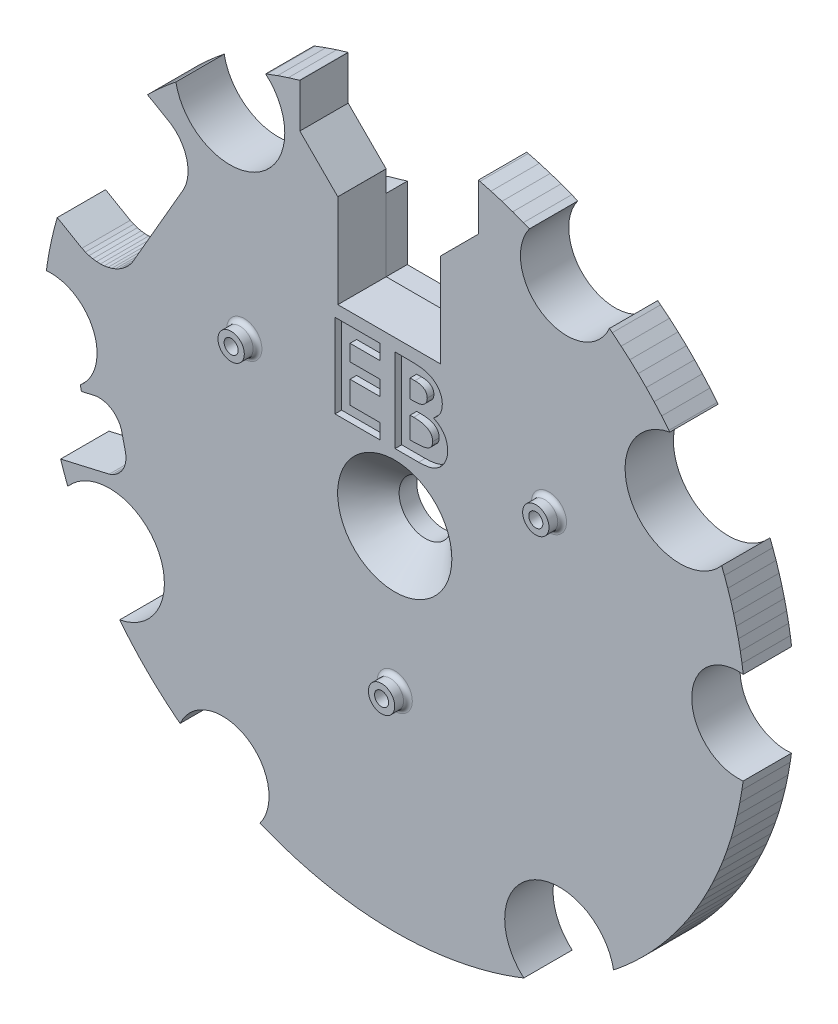
SolidWorks part; units mm, degrees
ref_plane "Płaszczyzna przednia" through (0, 0, 0) normal (0, 0, 1) x (1, 0, 0)
ref_plane "Płaszczyzna górna" through (0, 0, 0) normal (0, 1, 0) x (1, 0, 0)
ref_plane "Płaszczyzna prawa" through (0, 0, 0) normal (1, 0, 0) x (0, 0, -1)
sketch "mandaryna baza " plane through (0, 0, 0) normal (0, 0, 1) x (1, 0, 0)
  line L0 (16.9072, 3.25) -> (54.9039, 3.25)
  line L1 (30.2665, 45.9232) -> (11.2682, 13.017)
  line L2 (5.639, 16.267) -> (24.6374, 49.1732)
  line L3 (-24.6374, 49.1732) -> (-5.639, 16.267)
  line L4 (-11.2682, 13.017) -> (-30.2665, 45.9232)
  line L5 (-54.9039, 3.25) -> (-16.9072, 3.25)
  line L6 (4.5506, 66.6591) -> (4.5491, 66.657) construction
  line L7 (24.4667, 51.9252) -> (4.5506, 66.6591) construction
  line L8 (5.8555, 16.142) -> (24.861, 49.0605) construction
  line L9 (-24.861, 49.0605) -> (-5.8555, 16.142) construction
  line L10 (-4.5491, 66.657) -> (-4.5506, 66.6591) construction
  line L11 (30.0571, 46.0605) -> (11.0517, 13.142) construction
  line L12 (67.2135, 4.9608) -> (71.9198, 8.4424) construction
  line L13 (16.9072, 3) -> (54.9181, 3) construction
  line L14 (-16.9072, -3.25) -> (-54.9039, -3.25)
  line L15 (-30.2665, -45.9232) -> (-11.2682, -13.017)
  line L16 (54.9181, -3) -> (16.9072, -3) construction
  line L17 (71.9198, -8.4424) -> (67.2135, -4.9608) construction
  line L18 (11.0517, -13.142) -> (30.0571, -46.0605) construction
  line L19 (-5.639, -16.267) -> (-24.6374, -49.1732)
  line L20 (24.6374, -49.1732) -> (5.639, -16.267)
  line L21 (11.2682, -13.017) -> (30.2665, -45.9232)
  line L22 (54.9039, -3.25) -> (16.9072, -3.25)
  line L23 (4.5506, -66.6591) -> (24.4667, -51.9252) construction
  line L24 (4.5491, -66.657) -> (4.5506, -66.6591) construction
  line L25 (-4.5506, -66.6591) -> (-4.5491, -66.657) construction
  line L26 (-24.4667, -51.9252) -> (-4.5506, -66.6591) construction
  line L27 (-67.2135, -4.9608) -> (-71.9198, -8.4424) construction
  line L28 (-16.9072, -3) -> (-54.9181, -3) construction
  line L29 (-54.9181, 3) -> (-16.9072, 3) construction
  line L30 (-71.9198, 8.4424) -> (-67.2135, 4.9608) construction
  line L31 (-11.0517, 13.142) -> (-30.0571, 46.0605) construction
  line L37 (-13.1504, 53.4048) -> (-13.1504, 36.9511)
  line L38 (-13.1504, 36.9511) -> (10.6176, 36.9511)
  line L39 (10.6176, 36.9511) -> (10.6176, 53.9654)
  circle A0 centre (0, 0) radius 85 construction
  circle A1 centre (0, 0) radius 6 construction
  arc A2 (11.2682, 13.017) -> (16.9072, 3.25) centre (16.9072, 9.7614) ccw
  arc A3 (-5.639, 16.267) -> (5.639, 16.267) centre (0, 19.5227) ccw
  arc A4 (-16.9072, 3.25) -> (-11.2682, 13.017) centre (-16.9072, 9.7614) ccw
  arc A5 (25.0093, 49.3174) -> (24.4667, 51.9252) centre (23.2772, 50.3174) ccw construction
  arc A6 (-5.8555, 16.142) -> (5.8555, 16.142) centre (0, 19.5227) ccw construction
  arc A7 (-4.5491, 66.657) -> (-0.4915, 64.6309) centre (-0.5295, 69.6307) ccw construction
  arc A8 (0.4915, 64.6309) -> (-0.4915, 64.6309) centre (0, 0) ccw construction
  arc A9 (0.4915, 64.6309) -> (4.5491, 66.657) centre (0.5295, 69.6307) ccw construction
  arc A10 (51.1946, 58.8482) -> (35.971, 56.3035) centre (44.6312, 51.3035) ccw construction
  arc A11 (75.6742, 18.9054) -> (51.1946, 58.8482) centre (0, 0) ccw construction
  arc A12 (71.9198, 8.4424) -> (75.6742, 18.9054) centre (65.9724, 16.4816) ccw construction
  arc A13 (61.2662, 3) -> (67.2135, 4.9608) centre (61.2662, 13) ccw construction
  arc A14 (11.0517, 13.142) -> (16.9072, 3) centre (16.9072, 9.7614) ccw construction
  arc A15 (-11.2682, -13.017) -> (-16.9072, -3.25) centre (-16.9072, -9.7614) ccw
  arc A16 (67.2135, -4.9608) -> (61.2662, -3) centre (61.2662, -13) ccw construction
  arc A17 (75.6742, -18.9054) -> (71.9198, -8.4424) centre (65.9724, -16.4816) ccw construction
  arc A18 (14.9118, -76.5613) -> (56.0831, -54.2097) centre (0, 0) ccw construction
  arc A19 (3, -66.7458) -> (14.9118, -76.5613) centre (13, -66.7458) ccw construction
  arc A20 (16.9072, -3) -> (11.0517, -13.142) centre (16.9072, -9.7614) ccw construction
  arc A21 (5.639, -16.267) -> (-5.639, -16.267) centre (0, -19.5227) ccw
  arc A22 (4.5491, -66.657) -> (0.4915, -64.6309) centre (0.5295, -69.6307) ccw construction
  arc A23 (-0.4915, -64.6309) -> (0.4915, -64.6309) centre (0, 0) ccw construction
  arc A24 (-0.4915, -64.6309) -> (-4.5491, -66.657) centre (-0.5295, -69.6307) ccw construction
  arc A25 (-25.0093, -49.3174) -> (-24.4667, -51.9252) centre (-23.2772, -50.3174) ccw construction
  arc A26 (5.8555, -16.142) -> (-5.8555, -16.142) centre (0, -19.5227) ccw construction
  arc A27 (16.9072, -3.25) -> (11.2682, -13.017) centre (16.9072, -9.7614) ccw
  arc A28 (30.2665, -45.9232) -> (54.9039, -3.25) centre (0, 0) ccw
  arc A29 (24.6374, 49.1732) -> (10.6176, 53.9654) centre (0, 0) ccw
  arc A30 (-51.1946, -58.8482) -> (-35.971, -56.3035) centre (-44.6312, -51.3035) ccw construction
  arc A31 (-75.6742, -18.9054) -> (-51.1946, -58.8482) centre (0, 0) ccw construction
  arc A32 (-71.9198, -8.4424) -> (-75.6742, -18.9054) centre (-65.9724, -16.4816) ccw construction
  arc A33 (-61.2662, -3) -> (-67.2135, -4.9608) centre (-61.2662, -13) ccw construction
  arc A34 (-11.0517, -13.142) -> (-16.9072, -3) centre (-16.9072, -9.7614) ccw construction
  arc A35 (-30.2665, 45.9232) -> (-54.9039, 3.25) centre (0, 0) ccw
  arc A36 (-54.9039, -3.25) -> (-30.2665, -45.9232) centre (0, 0) ccw
  arc A37 (-24.6374, -49.1732) -> (24.6374, -49.1732) centre (0, 0) ccw
  arc A38 (54.9039, 3.25) -> (30.2665, 45.9232) centre (0, 0) ccw
  arc A39 (-67.2135, 4.9608) -> (-61.2662, 3) centre (-61.2662, 13) ccw construction
  arc A40 (-75.6742, 18.9054) -> (-71.9198, 8.4424) centre (-65.9724, 16.4816) ccw construction
  arc A41 (-51.1946, 58.8482) -> (-75.6742, 18.9054) centre (0, 0) ccw construction
  arc A42 (-35.971, 56.3035) -> (-51.1946, 58.8482) centre (-44.6312, 51.3035) ccw construction
  arc A43 (-16.9072, 3) -> (-11.0517, 13.142) centre (-16.9072, 9.7614) ccw construction
  arc A44 (-13.1504, 53.4048) -> (-24.6374, 49.1732) centre (0, 0) ccw
extrude "Dodanie-wyciągnięcie1" add sketch "mandaryna baza " along normal blind 5
sketch "MB_wyciecia" plane through (0, 0, 0) normal (0, 0, 1) x (1, 0, 0)
  line L0 (-0.1242, -22.5327) -> (-0.3125, 0) construction
  line L1 (-34.4185, 20.0049) -> (-0.3125, 0) construction
  line L2 (13.0498, 7.7147) -> (34.7962, 20.27) construction
  line L7 (-35.0924, 72.0577) -> (-32.5738, 67.4522)
  line L8 (-42.3633, 62.4733) -> (-44.721, 66.557)
  line L9 (19.0018, 77.646) -> (19.0018, 67.2099)
  line L10 (19.0018, 67.2099) -> (10.3758, 58.5839)
  line L11 (10.3758, 58.5839) -> (10.3758, 37.3074)
  line L12 (10.3758, 37.3074) -> (-12.9922, 37.3074)
  line L13 (-12.9922, 37.3074) -> (-12.9922, 58.5739)
  line L14 (-12.9922, 58.5739) -> (-21.6382, 67.2099)
  line L15 (-21.6382, 67.2099) -> (-21.7619, 77.0835)
  line L19 (42.2923, -62.1866) -> (44.5033, -66.2834)
  line L20 (-58.3058, 54.9924) -> (-50.9165, 49.4506)
  line L21 (-70.2019, 38.6255) -> (-62.5311, 33.1574)
  line L23 (-74.5615, -9.724) -> (-68.7602, -8.3848)
  line L24 (-76.1011, -24.6775) -> (-65.5639, -22.245)
  line L25 (67.774, 32.961) -> (71.6123, 35.0537)
  line L26 (62.1773, 42.4277) -> (65.9654, 44.8239)
  line L28 (32.3345, -66.7767) -> (34.11, -72.1952)
  line L29 (-62.2802, -42.12) -> (-66.1005, -44.9806)
  line L30 (-67.4562, -32.4335) -> (-72.2043, -34.4007)
  line L31 (-58.3058, 54.9924) -> (-58.3719, 55.055)
  line L32 (-70.2019, 38.6255) -> (-70.3266, 38.7295)
  line L34 (-76.1011, -24.6775) -> (-76.3992, -24.7542)
  line L35 (-72.2043, -34.4007) -> (-72.5196, -34.4687)
  line L36 (-66.1005, -44.9806) -> (-66.3559, -45.1687)
  line L37 (34.11, -72.1952) -> (34.1253, -72.2217)
  arc A1 (-42.3633, 62.4733) -> (-32.5738, 67.4522) centre (-37.5482, 65.1194) ccw
  arc A3 (-62.5311, 33.1574) -> (-50.9165, 49.4506) centre (-56.5654, 41.1911) ccw
  arc A4 (-65.5639, -22.245) -> (-68.7602, -8.3848) centre (-67.0693, -15.2935) ccw
  arc A5 (-62.2802, -42.12) -> (-67.4562, -32.4335) centre (-64.9966, -37.3454) ccw
  arc A7 (62.1773, 42.4277) -> (67.774, 32.961) centre (64.9255, 37.6647) ccw
  arc A8 (42.2923, -62.1866) -> (32.3345, -66.7767) centre (37.4627, -64.8056) ccw
  arc A9 (-21.7619, 77.0835) -> (-35.0924, 72.0577) centre (-0.3125, 0) ccw
  arc A10 (-44.721, 66.557) -> (-58.3719, 55.055) centre (-0.3125, 0) ccw
  arc A11 (-70.3266, 38.7295) -> (-79.6124, 10.6528) centre (-0.3125, 0) ccw
  arc A12 (-76.3992, -24.7542) -> (-72.5196, -34.4687) centre (-0.3125, 0) ccw
  arc A13 (-66.3559, -45.1687) -> (-48.9339, -63.5445) centre (-0.3125, 0) ccw
  arc A14 (44.5033, -66.2834) -> (78.9866, -10.6577) centre (-0.3125, 0) ccw
  arc A15 (65.9654, 44.8239) -> (48.7749, 63.1852) centre (-0.3125, 0) ccw
  arc A16 (79.0174, 10.4265) -> (78.9866, -10.6577) centre (78.1738, -0.1144) ccw
  arc A18 (-30.7368, -74.0021) -> (-48.9339, -63.5445) centre (-39.186, -67.6433) ccw
  arc A21 (30.5908, 73.8033) -> (48.7749, 63.1852) centre (39.186, 67.6433) ccw
  circle A22 centre (38.9878, -67.7577) radius 10.5746
  circle A23 centre (-38.9878, 67.7577) radius 10.5746
  arc A24 (30.5908, 73.8033) -> (19.0018, 77.646) centre (-0.3125, 0) ccw
  arc A25 (79.0174, 10.4265) -> (71.6123, 35.0537) centre (-0.3125, 0) ccw
  arc A26 (-30.7368, -74.0021) -> (34.1253, -72.2217) centre (-0.3125, 0) ccw
  arc A28 (-74.5615, -9.724) -> (-79.6124, 10.6528) centre (-78.3301, 0.1563) ccw
  arc A29 (-84.5664, -8.3092) -> (-82.6226, -9.4789) centre (-78.1738, 0.1144) ccw
  point P46 (0, 0)
  dimension "D6" = 10.9879
  dimension "D7" = 10.9884
  dimension "D8" = 20.013
  dimension "D9" = 14.2253
  dimension "D10" = 10.9979
  dimension "D11" = 160.0243
  dimension "D3" = 80.0122
  dimension "D2" = 39.54
  dimension "D4" = 6
  dimension "D13" = 40.54
  dimension "D15" = 39.54
sketch "EB_" plane through (0, 0, 0) normal (0, 0, 1) x (1, 0, 0)
  line L0 (0, 0) -> (-22.7294, 43.3106) construction
  line L1 (0, 0) -> (25.5306, 43.3106) construction
  line L2 (0, 0) -> (-19.5544, -22.7294)
  line L3 (0, 0) -> (22.3556, -22.7294)
  line L4 (-71.5796, -7.9834) -> (-71.3126, -9.14)
  line L5 (-71.3126, -9.14) -> (-68.5352, -8.4988)
  line L660 (-59.4357, 22.62) -> (-59.654, 22.2418)
  line L661 (-59.654, 22.2418) -> (-60.1628, 21.5318)
  line L662 (-60.1628, 21.5318) -> (-60.7387, 20.8751)
  line L663 (-60.7387, 20.8751) -> (-61.3762, 20.278)
  line L664 (-61.3762, 20.278) -> (-62.0692, 19.7462)
  line L665 (-62.0692, 19.7462) -> (-62.811, 19.285)
  line L666 (-62.811, 19.285) -> (-63.5944, 18.8986)
  line L667 (-63.5944, 18.8986) -> (-64.4119, 18.591)
  line L668 (-64.4119, 18.591) -> (-65.2556, 18.3649)
  line L669 (-65.2556, 18.3649) -> (-66.1174, 18.2226)
  line L670 (-66.1174, 18.2226) -> (-66.989, 18.1655)
  line L671 (-66.989, 18.1655) -> (-67.862, 18.1941)
  line L672 (-67.862, 18.1941) -> (-68.728, 18.3081)
  line L673 (-68.728, 18.3081) -> (-69.5787, 18.5064)
  line L674 (-69.5787, 18.5064) -> (-70.4058, 18.7872)
  line L675 (-70.4058, 18.7872) -> (-71.2014, 19.1477)
  line L676 (-71.2014, 19.1477) -> (-71.5796, 19.366)
  line L677 (-71.5796, 19.366) -> (-76.8174, 22.3901)
  line L678 (-76.8174, 22.3901) -> (-76.8834, 22.1744)
  line L679 (-76.8834, 22.1744) -> (-77.5625, 19.6678)
  line L680 (-77.5625, 19.6678) -> (-78.1599, 17.1405)
  line L681 (-78.1599, 17.1405) -> (-78.6749, 14.5952)
  line L682 (-78.6749, 14.5952) -> (-79.1071, 12.0345)
  line L683 (-79.1071, 12.0345) -> (-79.2897, 10.6872)
  line L693 (-68.5352, -8.4988) -> (-68.1939, -8.42)
  line L694 (-68.1939, -8.42) -> (-67.4966, -8.3528)
  line L695 (-67.4966, -8.3528) -> (-66.7965, -8.3773)
  line L696 (-66.7965, -8.3773) -> (-66.1056, -8.4929)
  line L697 (-66.1056, -8.4929) -> (-65.4357, -8.6977)
  line L698 (-65.4357, -8.6977) -> (-64.7982, -8.9882)
  line L699 (-64.7982, -8.9882) -> (-64.2042, -9.3594)
  line L700 (-64.2042, -9.3594) -> (-63.6636, -9.805)
  line L701 (-63.6636, -9.805) -> (-63.1859, -10.3174)
  line L702 (-63.1859, -10.3174) -> (-62.7791, -10.8877)
  line L703 (-62.7791, -10.8877) -> (-62.4502, -11.5062)
  line L704 (-62.4502, -11.5062) -> (-62.2049, -12.1624)
  line L705 (-62.2049, -12.1624) -> (-62.1261, -12.5037)
  line L706 (-62.1261, -12.5037) -> (-61.3306, -15.949)
  line L707 (-61.3306, -15.949) -> (-61.2518, -16.2903)
  line L708 (-61.2518, -16.2903) -> (-61.1847, -16.9876)
  line L709 (-61.1847, -16.9876) -> (-61.2092, -17.6877)
  line L710 (-61.2092, -17.6877) -> (-61.3248, -18.3787)
  line L711 (-61.3248, -18.3787) -> (-61.5296, -19.0486)
  line L712 (-61.5296, -19.0486) -> (-61.8201, -19.686)
  line L713 (-61.8201, -19.686) -> (-62.1913, -20.2801)
  line L714 (-62.1913, -20.2801) -> (-62.6369, -20.8206)
  line L715 (-62.6369, -20.8206) -> (-63.1492, -21.2984)
  line L716 (-63.1492, -21.2984) -> (-63.7196, -21.7052)
  line L717 (-63.7196, -21.7052) -> (-64.3381, -22.0341)
  line L718 (-64.3381, -22.0341) -> (-64.9942, -22.2794)
  line L719 (-64.9942, -22.2794) -> (-65.3355, -22.3582)
  line L720 (-65.3355, -22.3582) -> (-76.0559, -24.8332)
  line L721 (-76.0559, -24.8332) -> (-75.5463, -26.3728)
  line L722 (-75.5463, -26.3728) -> (-74.6507, -28.8104)
  line L723 (-74.6507, -28.8104) -> (-74.4178, -29.3858)
  line L756 (-62.6093, -49.8114) -> (-61.8317, -50.7929)
  line L757 (-61.8317, -50.7929) -> (-60, -52.944)
  line L758 (-60, -52.944) -> (-58.0936, -55.0292)
  line L759 (-58.0936, -55.0292) -> (-56.1147, -57.0457)
  line L760 (-56.1147, -57.0457) -> (-54.0659, -58.9911)
  line L761 (-54.0659, -58.9911) -> (-51.9496, -60.863)
  line L762 (-51.9496, -60.863) -> (-49.7687, -62.659)
  line L763 (-49.7687, -62.659) -> (-48.854, -63.3595)
  line L770 (-30.6643, -73.9045) -> (-30.3309, -74.048)
  line L771 (-30.3309, -74.048) -> (-27.6979, -75.0726)
  line L772 (-27.6979, -75.0726) -> (-25.0304, -76.0036)
  line L773 (-25.0304, -76.0036) -> (-22.3317, -76.8399)
  line L774 (-22.3317, -76.8399) -> (-19.6051, -77.5804)
  line L775 (-19.6051, -77.5804) -> (-16.8541, -78.2241)
  line L776 (-16.8541, -78.2241) -> (-14.0821, -78.7703)
  line L777 (-14.0821, -78.7703) -> (-11.2926, -79.2184)
  line L778 (-11.2926, -79.2184) -> (-8.4889, -79.5676)
  line L779 (-8.4889, -79.5676) -> (-5.6747, -79.8177)
  line L780 (-5.6747, -79.8177) -> (-2.8534, -79.9683)
  line L781 (-2.8534, -79.9683) -> (-0.0286, -80.0192)
  line L782 (-0.0286, -80.0192) -> (2.7963, -79.9703)
  line L783 (2.7963, -79.9703) -> (5.6177, -79.8218)
  line L784 (5.6177, -79.8218) -> (8.4321, -79.5737)
  line L785 (8.4321, -79.5737) -> (11.236, -79.2264)
  line L786 (11.236, -79.2264) -> (14.0259, -78.7804)
  line L787 (14.0259, -78.7804) -> (16.7983, -78.2361)
  line L788 (16.7983, -78.2361) -> (19.5497, -77.5943)
  line L789 (19.5497, -77.5943) -> (22.2768, -76.8558)
  line L790 (22.2768, -76.8558) -> (24.9761, -76.0215)
  line L791 (24.9761, -76.0215) -> (27.6443, -75.0924)
  line L792 (27.6443, -75.0924) -> (29.3845, -74.4166)
  line L825 (49.8125, -62.6148) -> (50.2037, -62.3107)
  line L826 (50.2037, -62.3107) -> (52.3536, -60.5156)
  line L827 (52.3536, -60.5156) -> (54.4394, -58.6463)
  line L828 (54.4394, -58.6463) -> (56.4584, -56.7052)
  line L829 (56.4584, -56.7052) -> (58.4083, -54.6947)
  line L830 (58.4083, -54.6947) -> (60.2867, -52.6171)
  line L831 (60.2867, -52.6171) -> (62.0911, -50.475)
  line L832 (62.0911, -50.475) -> (63.8195, -48.2711)
  line L833 (63.8195, -48.2711) -> (65.4698, -46.0081)
  line L834 (65.4698, -46.0081) -> (67.0398, -43.6887)
  line L835 (67.0398, -43.6887) -> (68.5277, -41.3158)
  line L836 (68.5277, -41.3158) -> (69.9316, -38.8923)
  line L837 (69.9316, -38.8923) -> (71.2498, -36.4211)
  line L838 (71.2498, -36.4211) -> (72.4808, -33.9053)
  line L839 (72.4808, -33.9053) -> (73.623, -31.348)
  line L840 (73.623, -31.348) -> (74.6749, -28.7523)
  line L841 (74.6749, -28.7523) -> (75.6354, -26.1213)
  line L842 (75.6354, -26.1213) -> (76.5032, -23.4583)
  line L843 (76.5032, -23.4583) -> (77.2773, -20.7666)
  line L844 (77.2773, -20.7666) -> (77.9567, -18.0495)
  line L845 (77.9567, -18.0495) -> (78.5407, -15.3102)
  line L846 (78.5407, -15.3102) -> (79.0284, -12.5522)
  line L847 (79.0284, -12.5522) -> (79.2994, -10.6289)
  line L856 (79.3336, 10.3964) -> (79.0449, 12.4201)
  line L857 (79.0449, 12.4201) -> (78.6613, 14.6547)
  line L858 (78.6613, 14.6547) -> (78.2145, 16.8775)
  line L859 (78.2145, 16.8775) -> (77.7049, 19.0868)
  line L860 (77.7049, 19.0868) -> (77.1329, 21.2808)
  line L861 (77.1329, 21.2808) -> (76.499, 23.4576)
  line L862 (76.499, 23.4576) -> (75.8037, 25.6157)
  line L863 (75.8037, 25.6157) -> (75.0475, 27.7531)
  line L864 (75.0475, 27.7531) -> (74.4174, 29.3854)
  line L897 (62.6156, 49.8127) -> (62.4143, 50.0722)
  line L898 (62.4143, 50.0722) -> (60.7549, 52.0732)
  line L899 (60.7549, 52.0732) -> (59.0313, 54.0192)
  line L900 (59.0313, 54.0192) -> (57.2455, 55.9082)
  line L901 (57.2455, 55.9082) -> (55.3992, 57.7382)
  line L902 (55.3992, 57.7382) -> (53.4945, 59.5072)
  line L903 (53.4945, 59.5072) -> (51.5333, 61.2135)
  line L904 (51.5333, 61.2135) -> (49.5177, 62.8551)
  line L905 (49.5177, 62.8551) -> (48.8544, 63.3604)
  line L913 (30.6602, 73.899) -> (29.2981, 74.4606)
  line L914 (29.2981, 74.4606) -> (26.864, 75.373)
  line L915 (26.864, 75.373) -> (24.4015, 76.2059)
  line L916 (24.4015, 76.2059) -> (21.9132, 76.9583)
  line L917 (21.9132, 76.9583) -> (19.4018, 77.6295)
  line L918 (19.4018, 77.6295) -> (19.0436, 77.7128)
  line L919 (19.0436, 77.7128) -> (19.0437, 67.0537)
  line L920 (19.0437, 67.0537) -> (10.4176, 58.4277)
  line L921 (10.4176, 58.4277) -> (10.4176, 37.1511)
  line L922 (10.4176, 37.1511) -> (-12.9504, 37.1511)
  line L923 (-12.9504, 37.1511) -> (-12.9504, 58.4177)
  line L924 (-12.9504, 58.4177) -> (-12.9604, 58.4177)
  line L925 (-12.9604, 58.4177) -> (-21.5964, 67.0537)
  line L926 (-21.5964, 67.0537) -> (-21.5964, 77.0457)
  line L927 (-21.5964, 77.0457) -> (-21.7211, 77.0127)
  line L928 (-21.7211, 77.0127) -> (-24.2112, 76.2665)
  line L929 (-24.2112, 76.2665) -> (-26.6758, 75.4398)
  line L930 (-26.6758, 75.4398) -> (-29.1122, 74.5335)
  line L931 (-29.1122, 74.5335) -> (-29.3887, 74.4203)
  line L964 (-49.8133, 62.6189) -> (-49.8986, 62.5531)
  line L965 (-49.8986, 62.5531) -> (-51.9022, 60.9009)
  line L966 (-51.9022, 60.9009) -> (-53.8511, 59.1846)
  line L967 (-53.8511, 59.1846) -> (-55.7433, 57.406)
  line L968 (-55.7433, 57.406) -> (-56.2765, 56.8712)
  line L969 (-56.2765, 56.8712) -> (-51.5136, 54.1214)
  line L970 (-51.5136, 54.1214) -> (-51.1354, 53.903)
  line L971 (-51.1354, 53.903) -> (-50.4254, 53.3942)
  line L972 (-50.4254, 53.3942) -> (-49.7687, 52.8183)
  line L973 (-49.7687, 52.8183) -> (-49.1716, 52.1808)
  line L974 (-49.1716, 52.1808) -> (-48.6398, 51.4878)
  line L975 (-48.6398, 51.4878) -> (-48.1786, 50.746)
  line L976 (-48.1786, 50.746) -> (-47.7923, 49.9626)
  line L977 (-47.7923, 49.9626) -> (-47.4846, 49.1452)
  line L978 (-47.4846, 49.1452) -> (-47.2585, 48.3014)
  line L979 (-47.2585, 48.3014) -> (-47.1162, 47.4396)
  line L980 (-47.1162, 47.4396) -> (-47.0591, 46.568)
  line L981 (-47.0591, 46.568) -> (-47.0877, 45.695)
  line L982 (-47.0877, 45.695) -> (-47.2017, 44.829)
  line L983 (-47.2017, 44.829) -> (-47.4, 43.9784)
  line L984 (-47.4, 43.9784) -> (-47.6808, 43.1512)
  line L985 (-47.6808, 43.1512) -> (-48.0413, 42.3556)
  line L986 (-48.0413, 42.3556) -> (-48.2597, 41.9774)
  line L987 (-48.2597, 41.9774) -> (-59.4357, 22.62)
  arc A0 (64.3736, 47.5139) -> (73.3082, 32.0629) centre (64.9348, 37.5297) ccw construction
  circle A3 centre (0, -32.54) radius 1.6
  circle A4 centre (35.1087, 20.27) radius 1.6
  circle A5 centre (-34.2427, 19.77) radius 1.6
  arc A7 (59.3647, 45.8348) -> (-28.5574, 69.3504) centre (0, 0) ccw construction
  arc A9 (-45.8348, 59.3647) -> (-69.3504, -28.5574) centre (0, 0) ccw construction
  arc A10 (-67.5212, -32.6479) -> (69.3504, 28.5574) centre (0, 0) ccw construction
  arc A12 (-30.6643, -73.9045) -> (-48.854, -63.3595) centre (-39.186, -67.6433) ccw
  arc A13 (79.3336, 10.3964) -> (79.2994, -10.6289) centre (78.1738, -0.1144) ccw
  arc A14 (30.6602, 73.899) -> (48.8544, 63.3604) centre (39.186, 67.6433) ccw
  arc A15 (-71.5796, -7.9834) -> (-79.2897, 10.6872) centre (-78.3301, 0.1563) ccw
  arc A16 (62.6156, 49.8127) -> (74.4174, 29.3854) centre (64.9348, 37.5297) ccw
  arc A17 (49.8125, -62.6148) -> (29.3845, -74.4166) centre (37.5297, -64.9348) ccw
  arc A18 (-62.6093, -49.8114) -> (-74.4178, -29.3858) centre (-64.9348, -37.5297) ccw
  arc A19 (-49.8133, 62.6189) -> (-29.3887, 74.4203) centre (-37.5297, 64.9348) ccw
  point P38 (0, 0)
  point P80 (0, 0)
  dimension "D5" = 150
  dimension "D6" = 20
  dimension "D8" = 25
  dimension "D1" = 29.9833
  dimension "D2" = 31.881
  dimension "D3" = 50.2755
  dimension "D4" = 48.9125
  dimension "D9" = 4
extrude "Dodanie-wyciągnięcie2" add sketch "EB_" along direction (0, 0, 1) on the side of the normal blind 11 from offset 5
sketch "Szkic5" plane through (0, 0, 16) normal (0, 0, 1) x (1, 0, 0)
  circle A0 centre (-34.2427, 19.77) radius 1.6
  circle A1 centre (-34.2427, 19.77) radius 3
  circle A2 centre (35.1087, 20.27) radius 1.6
  circle A3 centre (35.1087, 20.27) radius 3
  circle A4 centre (0, -32.54) radius 1.6
  circle A5 centre (0, -32.54) radius 3
  dimension "D1" = 6
  dimension "D2" = 3.2
  dimension "D3" = 6
  dimension "D4" = 3.2
  dimension "D5" = 6
  dimension "D6" = 3.2
extrude "Dodanie-wyciągnięcie3" add sketch "Szkic5" along normal blind 3
sketch "Szkic6" plane through (0, 0, 16) normal (0, 0, 1) x (1, 0, 0)
  circle A0 centre (0, -32.54) radius 1.6 construction
  circle A1 centre (35.1087, 20.27) radius 1.6 construction
  circle A2 centre (-34.2427, 19.77) radius 1.6 construction
  circle A3 centre (0, -32.54) radius 1.6
  circle A4 centre (35.1087, 20.27) radius 1.6
  circle A5 centre (-34.2427, 19.77) radius 1.6
extrude "Wytnij-wyciągnięcie1" cut sketch "Szkic6" against normal through all
sketch "Szkic7" plane through (0, 0, 16) normal (0, 0, 1) x (1, 0, 0)
  circle A0 centre (0, 0) radius 6
  dimension "D1" = 12
extrude "Wytnij-wyciągnięcie2" cut sketch "Szkic7" against normal through all
chamfer "Sfazowanie1" distance 7 angle 45 1 edges at (6, 0, 16)
sketch "Szkic8" plane through (0, 0, 16) normal (0, 0, 1) x (1, 0, 0)
  line L181 (-71.5796, -7.9834) -> (-71.3126, -9.14)
  line L182 (-71.3126, -9.14) -> (-68.5352, -8.4988)
  line L183 (-68.5352, -8.4988) -> (-68.1939, -8.42)
  line L184 (-68.1939, -8.42) -> (-67.4966, -8.3528)
  line L185 (-67.4966, -8.3528) -> (-66.7965, -8.3773)
  line L186 (-66.7965, -8.3773) -> (-66.1056, -8.4929)
  line L187 (-66.1056, -8.4929) -> (-65.4357, -8.6977)
  line L188 (-65.4357, -8.6977) -> (-64.7982, -8.9882)
  line L189 (-64.7982, -8.9882) -> (-64.2042, -9.3594)
  line L190 (-64.2042, -9.3594) -> (-63.6636, -9.805)
  line L191 (-63.6636, -9.805) -> (-63.1859, -10.3174)
  line L192 (-63.1859, -10.3174) -> (-62.7791, -10.8877)
  line L193 (-62.7791, -10.8877) -> (-62.4502, -11.5062)
  line L194 (-62.4502, -11.5062) -> (-62.2049, -12.1624)
  line L195 (-62.2049, -12.1624) -> (-62.1261, -12.5037)
  line L196 (-62.1261, -12.5037) -> (-61.3306, -15.949)
  line L197 (-61.3306, -15.949) -> (-61.2518, -16.2903)
  line L198 (-61.2518, -16.2903) -> (-61.1847, -16.9876)
  line L199 (-61.1847, -16.9876) -> (-61.2092, -17.6877)
  line L200 (-61.2092, -17.6877) -> (-61.3248, -18.3787)
  line L201 (-61.3248, -18.3787) -> (-61.5296, -19.0486)
  line L202 (-61.5296, -19.0486) -> (-61.8201, -19.686)
  line L203 (-61.8201, -19.686) -> (-62.1913, -20.2801)
  line L204 (-62.1913, -20.2801) -> (-62.6369, -20.8206)
  line L205 (-62.6369, -20.8206) -> (-63.1492, -21.2984)
  line L206 (-63.1492, -21.2984) -> (-63.7196, -21.7052)
  line L207 (-63.7196, -21.7052) -> (-64.3381, -22.0341)
  line L208 (-64.3381, -22.0341) -> (-64.9942, -22.2794)
  line L209 (-64.9942, -22.2794) -> (-65.3355, -22.3582)
  line L210 (-65.3355, -22.3582) -> (-76.0559, -24.8332)
  line L211 (-76.0559, -24.8332) -> (-75.5463, -26.3728)
  line L212 (-75.5463, -26.3728) -> (-74.6507, -28.8104)
  line L213 (-74.6507, -28.8104) -> (-74.4178, -29.3858)
  line L216 (-62.6093, -49.8114) -> (-61.8317, -50.7929)
  line L217 (-61.8317, -50.7929) -> (-60, -52.944)
  line L218 (-60, -52.944) -> (-58.0936, -55.0292)
  line L219 (-58.0936, -55.0292) -> (-56.1147, -57.0457)
  line L220 (-56.1147, -57.0457) -> (-54.0659, -58.9911)
  line L221 (-54.0659, -58.9911) -> (-51.9496, -60.863)
  line L222 (-51.9496, -60.863) -> (-49.7687, -62.659)
  line L223 (-49.7687, -62.659) -> (-48.854, -63.3595)
  line L224 (-30.6643, -73.9045) -> (-30.3309, -74.048)
  line L225 (-30.3309, -74.048) -> (-27.6979, -75.0726)
  line L226 (-27.6979, -75.0726) -> (-25.0304, -76.0036)
  line L227 (-25.0304, -76.0036) -> (-22.3317, -76.8399)
  line L228 (-22.3317, -76.8399) -> (-19.6051, -77.5804)
  line L229 (-19.6051, -77.5804) -> (-16.8541, -78.2241)
  line L230 (-16.8541, -78.2241) -> (-14.0821, -78.7703)
  line L231 (-14.0821, -78.7703) -> (-11.2926, -79.2184)
  line L232 (-11.2926, -79.2184) -> (-8.4889, -79.5676)
  line L233 (-8.4889, -79.5676) -> (-5.6747, -79.8177)
  line L234 (-5.6747, -79.8177) -> (-2.8534, -79.9683)
  line L235 (-2.8534, -79.9683) -> (-0.0286, -80.0192)
  line L236 (-0.0286, -80.0192) -> (2.7963, -79.9703)
  line L237 (2.7963, -79.9703) -> (5.6177, -79.8218)
  line L238 (5.6177, -79.8218) -> (8.4321, -79.5737)
  line L239 (8.4321, -79.5737) -> (11.236, -79.2264)
  line L240 (11.236, -79.2264) -> (14.0259, -78.7804)
  line L241 (14.0259, -78.7804) -> (16.7983, -78.2361)
  line L242 (16.7983, -78.2361) -> (19.5497, -77.5943)
  line L243 (19.5497, -77.5943) -> (22.2768, -76.8558)
  line L244 (22.2768, -76.8558) -> (24.9761, -76.0215)
  line L245 (24.9761, -76.0215) -> (27.6443, -75.0924)
  line L246 (27.6443, -75.0924) -> (29.3845, -74.4166)
  line L249 (49.8125, -62.6148) -> (50.2037, -62.3107)
  line L250 (50.2037, -62.3107) -> (52.3536, -60.5156)
  line L251 (52.3536, -60.5156) -> (54.4394, -58.6463)
  line L252 (54.4394, -58.6463) -> (56.4584, -56.7052)
  line L253 (56.4584, -56.7052) -> (58.4083, -54.6947)
  line L254 (58.4083, -54.6947) -> (60.2867, -52.6171)
  line L255 (60.2867, -52.6171) -> (62.0911, -50.475)
  line L256 (62.0911, -50.475) -> (63.8195, -48.2711)
  line L257 (63.8195, -48.2711) -> (65.4698, -46.0081)
  line L258 (65.4698, -46.0081) -> (67.0398, -43.6887)
  line L259 (67.0398, -43.6887) -> (68.5277, -41.3158)
  line L260 (68.5277, -41.3158) -> (69.9316, -38.8923)
  line L261 (69.9316, -38.8923) -> (71.2498, -36.4211)
  line L262 (71.2498, -36.4211) -> (72.4808, -33.9053)
  line L263 (72.4808, -33.9053) -> (73.623, -31.348)
  line L264 (73.623, -31.348) -> (74.6749, -28.7523)
  line L265 (74.6749, -28.7523) -> (75.6354, -26.1213)
  line L266 (75.6354, -26.1213) -> (76.5032, -23.4583)
  line L267 (76.5032, -23.4583) -> (77.2773, -20.7666)
  line L268 (77.2773, -20.7666) -> (77.9567, -18.0495)
  line L269 (77.9567, -18.0495) -> (78.5407, -15.3102)
  line L270 (78.5407, -15.3102) -> (79.0284, -12.5522)
  line L271 (79.0284, -12.5522) -> (79.2994, -10.6289)
  line L272 (79.3336, 10.3964) -> (79.0449, 12.4201)
  line L273 (79.0449, 12.4201) -> (78.6613, 14.6547)
  line L274 (78.6613, 14.6547) -> (78.2145, 16.8775)
  line L275 (78.2145, 16.8775) -> (77.7049, 19.0868)
  line L276 (77.7049, 19.0868) -> (77.1329, 21.2808)
  line L277 (77.1329, 21.2808) -> (76.499, 23.4576)
  line L278 (76.499, 23.4576) -> (75.8037, 25.6157)
  line L279 (75.8037, 25.6157) -> (75.0475, 27.7531)
  line L280 (75.0475, 27.7531) -> (74.4174, 29.3854)
  line L284 (62.6156, 49.8127) -> (62.4143, 50.0722)
  line L285 (62.4143, 50.0722) -> (60.7549, 52.0732)
  line L286 (60.7549, 52.0732) -> (59.0313, 54.0192)
  line L287 (59.0313, 54.0192) -> (57.2455, 55.9082)
  line L288 (57.2455, 55.9082) -> (55.3992, 57.7382)
  line L289 (55.3992, 57.7382) -> (53.4945, 59.5072)
  line L290 (53.4945, 59.5072) -> (51.5333, 61.2135)
  line L291 (51.5333, 61.2135) -> (49.5177, 62.8551)
  line L292 (49.5177, 62.8551) -> (48.8544, 63.3604)
  line L293 (30.6602, 73.899) -> (29.2981, 74.4606)
  line L294 (29.2981, 74.4606) -> (26.864, 75.373)
  line L295 (26.864, 75.373) -> (24.4015, 76.2059)
  line L296 (24.4015, 76.2059) -> (21.9132, 76.9583)
  line L297 (21.9132, 76.9583) -> (19.4018, 77.6295)
  line L298 (19.4018, 77.6295) -> (19.0436, 77.7128)
  line L299 (19.0436, 77.7128) -> (19.0437, 67.0537)
  line L300 (19.0437, 67.0537) -> (10.4176, 58.4277)
  line L301 (10.4176, 58.4277) -> (10.4176, 37.1511)
  line L302 (10.4176, 37.1511) -> (-12.9504, 37.1511)
  line L303 (-12.9504, 37.1511) -> (-12.9504, 58.4177)
  line L304 (-12.9504, 58.4177) -> (-12.9604, 58.4177)
  line L305 (-12.9604, 58.4177) -> (-21.5964, 67.0537)
  line L306 (-21.5964, 67.0537) -> (-21.5964, 77.0457)
  line L307 (-21.5964, 77.0457) -> (-21.7211, 77.0127)
  line L308 (-21.7211, 77.0127) -> (-24.2112, 76.2665)
  line L309 (-24.2112, 76.2665) -> (-26.6758, 75.4398)
  line L310 (-26.6758, 75.4398) -> (-29.1122, 74.5335)
  line L311 (-29.1122, 74.5335) -> (-29.3887, 74.4203)
  line L314 (-49.8133, 62.6189) -> (-49.8986, 62.5531)
  line L315 (-49.8986, 62.5531) -> (-51.9022, 60.9009)
  line L316 (-51.9022, 60.9009) -> (-53.8511, 59.1846)
  line L317 (-53.8511, 59.1846) -> (-55.7433, 57.406)
  line L318 (-55.7433, 57.406) -> (-56.2765, 56.8712)
  line L319 (-56.2765, 56.8712) -> (-51.5136, 54.1214)
  line L320 (-51.5136, 54.1214) -> (-51.1354, 53.903)
  line L321 (-51.1354, 53.903) -> (-50.4254, 53.3942)
  line L322 (-50.4254, 53.3942) -> (-49.7687, 52.8183)
  line L323 (-49.7687, 52.8183) -> (-49.1716, 52.1808)
  line L324 (-49.1716, 52.1808) -> (-48.6398, 51.4878)
  line L325 (-48.6398, 51.4878) -> (-48.1786, 50.746)
  line L326 (-48.1786, 50.746) -> (-47.7923, 49.9626)
  line L327 (-47.7923, 49.9626) -> (-47.4846, 49.1452)
  line L328 (-47.4846, 49.1452) -> (-47.2585, 48.3014)
  line L329 (-47.2585, 48.3014) -> (-47.1162, 47.4396)
  line L330 (-47.1162, 47.4396) -> (-47.0591, 46.568)
  line L331 (-47.0591, 46.568) -> (-47.0877, 45.695)
  line L332 (-47.0877, 45.695) -> (-47.2017, 44.829)
  line L333 (-47.2017, 44.829) -> (-47.4, 43.9784)
  line L334 (-47.4, 43.9784) -> (-47.6808, 43.1512)
  line L335 (-47.6808, 43.1512) -> (-48.0413, 42.3556)
  line L336 (-48.0413, 42.3556) -> (-48.2597, 41.9774)
  line L337 (-48.2597, 41.9774) -> (-59.4357, 22.62)
  line L338 (-59.4357, 22.62) -> (-59.654, 22.2418)
  line L339 (-59.654, 22.2418) -> (-60.1628, 21.5318)
  line L340 (-60.1628, 21.5318) -> (-60.7387, 20.8751)
  line L341 (-60.7387, 20.8751) -> (-61.3762, 20.278)
  line L342 (-61.3762, 20.278) -> (-62.0692, 19.7462)
  line L343 (-62.0692, 19.7462) -> (-62.811, 19.285)
  line L344 (-62.811, 19.285) -> (-63.5944, 18.8986)
  line L345 (-63.5944, 18.8986) -> (-64.4119, 18.591)
  line L346 (-64.4119, 18.591) -> (-65.2556, 18.3649)
  line L347 (-65.2556, 18.3649) -> (-66.1174, 18.2226)
  line L348 (-66.1174, 18.2226) -> (-66.989, 18.1655)
  line L349 (-66.989, 18.1655) -> (-67.862, 18.1941)
  line L350 (-67.862, 18.1941) -> (-68.728, 18.3081)
  line L351 (-68.728, 18.3081) -> (-69.5787, 18.5064)
  line L352 (-69.5787, 18.5064) -> (-70.4058, 18.7872)
  line L353 (-70.4058, 18.7872) -> (-71.2014, 19.1477)
  line L354 (-71.2014, 19.1477) -> (-71.5796, 19.366)
  line L355 (-71.5796, 19.366) -> (-76.8174, 22.3901)
  line L356 (-76.8174, 22.3901) -> (-76.8834, 22.1744)
  line L357 (-76.8834, 22.1744) -> (-77.5625, 19.6678)
  line L358 (-77.5625, 19.6678) -> (-78.1599, 17.1405)
  line L359 (-78.1599, 17.1405) -> (-78.6749, 14.5952)
  line L360 (-78.6749, 14.5952) -> (-79.1071, 12.0345)
  line L361 (-79.1071, 12.0345) -> (-79.2897, 10.6872)
  line L362 (-71.5796, -7.9834) -> (-71.3126, -9.14)
  line L363 (-71.3126, -9.14) -> (-68.5352, -8.4988)
  line L364 (-68.5352, -8.4988) -> (-68.1939, -8.42)
  line L365 (-68.1939, -8.42) -> (-67.4966, -8.3528)
  line L366 (-67.4966, -8.3528) -> (-66.7965, -8.3773)
  line L367 (-66.7965, -8.3773) -> (-66.1056, -8.4929)
  line L368 (-66.1056, -8.4929) -> (-65.4357, -8.6977)
  line L369 (-65.4357, -8.6977) -> (-64.7982, -8.9882)
  line L370 (-64.7982, -8.9882) -> (-64.2042, -9.3594)
  line L371 (-64.2042, -9.3594) -> (-63.6636, -9.805)
  line L372 (-63.6636, -9.805) -> (-63.1859, -10.3174)
  line L373 (-63.1859, -10.3174) -> (-62.7791, -10.8877)
  line L374 (-62.7791, -10.8877) -> (-62.4502, -11.5062)
  line L375 (-62.4502, -11.5062) -> (-62.2049, -12.1624)
  line L376 (-62.2049, -12.1624) -> (-62.1261, -12.5037)
  line L377 (-62.1261, -12.5037) -> (-61.3306, -15.949)
  line L378 (-61.3306, -15.949) -> (-61.2518, -16.2903)
  line L379 (-61.2518, -16.2903) -> (-61.1847, -16.9876)
  line L380 (-61.1847, -16.9876) -> (-61.2092, -17.6877)
  line L381 (-61.2092, -17.6877) -> (-61.3248, -18.3787)
  line L382 (-61.3248, -18.3787) -> (-61.5296, -19.0486)
  line L383 (-61.5296, -19.0486) -> (-61.8201, -19.686)
  line L384 (-61.8201, -19.686) -> (-62.1913, -20.2801)
  line L385 (-62.1913, -20.2801) -> (-62.6369, -20.8206)
  line L386 (-62.6369, -20.8206) -> (-63.1492, -21.2984)
  line L387 (-63.1492, -21.2984) -> (-63.7196, -21.7052)
  line L388 (-63.7196, -21.7052) -> (-64.3381, -22.0341)
  line L389 (-64.3381, -22.0341) -> (-64.9942, -22.2794)
  line L390 (-64.9942, -22.2794) -> (-65.3355, -22.3582)
  line L391 (-65.3355, -22.3582) -> (-76.0559, -24.8332)
  line L392 (-76.0559, -24.8332) -> (-75.5463, -26.3728)
  line L393 (-75.5463, -26.3728) -> (-74.6507, -28.8104)
  line L394 (-74.6507, -28.8104) -> (-74.4178, -29.3858)
  line L397 (-62.6093, -49.8114) -> (-61.8317, -50.7929)
  line L398 (-61.8317, -50.7929) -> (-60, -52.944)
  line L399 (-60, -52.944) -> (-58.0936, -55.0292)
  line L400 (-58.0936, -55.0292) -> (-56.1147, -57.0457)
  line L401 (-56.1147, -57.0457) -> (-54.0659, -58.9911)
  line L402 (-54.0659, -58.9911) -> (-51.9496, -60.863)
  line L403 (-51.9496, -60.863) -> (-49.7687, -62.659)
  line L404 (-49.7687, -62.659) -> (-48.854, -63.3595)
  line L405 (-30.6643, -73.9045) -> (-30.3309, -74.048)
  line L406 (-30.3309, -74.048) -> (-27.6979, -75.0726)
  line L407 (-27.6979, -75.0726) -> (-25.0304, -76.0036)
  line L408 (-25.0304, -76.0036) -> (-22.3317, -76.8399)
  line L409 (-22.3317, -76.8399) -> (-19.6051, -77.5804)
  line L410 (-19.6051, -77.5804) -> (-16.8541, -78.2241)
  line L411 (-16.8541, -78.2241) -> (-14.0821, -78.7703)
  line L412 (-14.0821, -78.7703) -> (-11.2926, -79.2184)
  line L413 (-11.2926, -79.2184) -> (-8.4889, -79.5676)
  line L414 (-8.4889, -79.5676) -> (-5.6747, -79.8177)
  line L415 (-5.6747, -79.8177) -> (-2.8534, -79.9683)
  line L416 (-2.8534, -79.9683) -> (-0.0286, -80.0192)
  line L417 (-0.0286, -80.0192) -> (2.7963, -79.9703)
  line L418 (2.7963, -79.9703) -> (5.6177, -79.8218)
  line L419 (5.6177, -79.8218) -> (8.4321, -79.5737)
  line L420 (8.4321, -79.5737) -> (11.236, -79.2264)
  line L421 (11.236, -79.2264) -> (14.0259, -78.7804)
  line L422 (14.0259, -78.7804) -> (16.7983, -78.2361)
  line L423 (16.7983, -78.2361) -> (19.5497, -77.5943)
  line L424 (19.5497, -77.5943) -> (22.2768, -76.8558)
  line L425 (22.2768, -76.8558) -> (24.9761, -76.0215)
  line L426 (24.9761, -76.0215) -> (27.6443, -75.0924)
  line L427 (27.6443, -75.0924) -> (29.3845, -74.4166)
  line L430 (49.8125, -62.6148) -> (50.2037, -62.3107)
  line L431 (50.2037, -62.3107) -> (52.3536, -60.5156)
  line L432 (52.3536, -60.5156) -> (54.4394, -58.6463)
  line L433 (54.4394, -58.6463) -> (56.4584, -56.7052)
  line L434 (56.4584, -56.7052) -> (58.4083, -54.6947)
  line L435 (58.4083, -54.6947) -> (60.2867, -52.6171)
  line L436 (60.2867, -52.6171) -> (62.0911, -50.475)
  line L437 (62.0911, -50.475) -> (63.8195, -48.2711)
  line L438 (63.8195, -48.2711) -> (65.4698, -46.0081)
  line L439 (65.4698, -46.0081) -> (67.0398, -43.6887)
  line L440 (67.0398, -43.6887) -> (68.5277, -41.3158)
  line L441 (68.5277, -41.3158) -> (69.9316, -38.8923)
  line L442 (69.9316, -38.8923) -> (71.2498, -36.4211)
  line L443 (71.2498, -36.4211) -> (72.4808, -33.9053)
  line L444 (72.4808, -33.9053) -> (73.623, -31.348)
  line L445 (73.623, -31.348) -> (74.6749, -28.7523)
  line L446 (74.6749, -28.7523) -> (75.6354, -26.1213)
  line L447 (75.6354, -26.1213) -> (76.5032, -23.4583)
  line L448 (76.5032, -23.4583) -> (77.2773, -20.7666)
  line L449 (77.2773, -20.7666) -> (77.9567, -18.0495)
  line L450 (77.9567, -18.0495) -> (78.5407, -15.3102)
  line L451 (78.5407, -15.3102) -> (79.0284, -12.5522)
  line L452 (79.0284, -12.5522) -> (79.2994, -10.6289)
  line L453 (79.3336, 10.3964) -> (79.0449, 12.4201)
  line L454 (79.0449, 12.4201) -> (78.6613, 14.6547)
  line L455 (78.6613, 14.6547) -> (78.2145, 16.8775)
  line L456 (78.2145, 16.8775) -> (77.7049, 19.0868)
  line L457 (77.7049, 19.0868) -> (77.1329, 21.2808)
  line L458 (77.1329, 21.2808) -> (76.499, 23.4576)
  line L459 (76.499, 23.4576) -> (75.8037, 25.6157)
  line L460 (75.8037, 25.6157) -> (75.0475, 27.7531)
  line L461 (75.0475, 27.7531) -> (74.4174, 29.3854)
  line L465 (62.6156, 49.8127) -> (62.4143, 50.0722)
  line L466 (62.4143, 50.0722) -> (60.7549, 52.0732)
  line L467 (60.7549, 52.0732) -> (59.0313, 54.0192)
  line L468 (59.0313, 54.0192) -> (57.2455, 55.9082)
  line L469 (57.2455, 55.9082) -> (55.3992, 57.7382)
  line L470 (55.3992, 57.7382) -> (53.4945, 59.5072)
  line L471 (53.4945, 59.5072) -> (51.5333, 61.2135)
  line L472 (51.5333, 61.2135) -> (49.5177, 62.8551)
  line L473 (49.5177, 62.8551) -> (48.8544, 63.3604)
  line L474 (30.6602, 73.899) -> (29.2981, 74.4606)
  line L475 (29.2981, 74.4606) -> (26.864, 75.373)
  line L476 (26.864, 75.373) -> (24.4015, 76.2059)
  line L477 (24.4015, 76.2059) -> (21.9132, 76.9583)
  line L478 (21.9132, 76.9583) -> (19.4018, 77.6295)
  line L479 (19.4018, 77.6295) -> (19.0436, 77.7128)
  line L480 (19.0436, 77.7128) -> (19.0437, 67.0537)
  line L481 (19.0437, 67.0537) -> (10.4176, 58.4277)
  line L482 (10.4176, 58.4277) -> (10.4176, 37.1511)
  line L483 (10.4176, 37.1511) -> (-12.9504, 37.1511)
  line L484 (-12.9504, 37.1511) -> (-12.9504, 58.4177)
  line L485 (-12.9504, 58.4177) -> (-12.9604, 58.4177)
  line L486 (-12.9604, 58.4177) -> (-21.5964, 67.0537)
  line L487 (-21.5964, 67.0537) -> (-21.5964, 77.0457)
  line L488 (-21.5964, 77.0457) -> (-21.7211, 77.0127)
  line L489 (-21.7211, 77.0127) -> (-24.2112, 76.2665)
  line L490 (-24.2112, 76.2665) -> (-26.6758, 75.4398)
  line L491 (-26.6758, 75.4398) -> (-29.1122, 74.5335)
  line L492 (-29.1122, 74.5335) -> (-29.3887, 74.4203)
  line L495 (-49.8133, 62.6189) -> (-49.8986, 62.5531)
  line L496 (-49.8986, 62.5531) -> (-51.9022, 60.9009)
  line L497 (-51.9022, 60.9009) -> (-53.8511, 59.1846)
  line L498 (-53.8511, 59.1846) -> (-55.7433, 57.406)
  line L499 (-55.7433, 57.406) -> (-56.2765, 56.8712)
  line L500 (-56.2765, 56.8712) -> (-51.5136, 54.1214)
  line L501 (-51.5136, 54.1214) -> (-51.1354, 53.903)
  line L502 (-51.1354, 53.903) -> (-50.4254, 53.3942)
  line L503 (-50.4254, 53.3942) -> (-49.7687, 52.8183)
  line L504 (-49.7687, 52.8183) -> (-49.1716, 52.1808)
  line L505 (-49.1716, 52.1808) -> (-48.6398, 51.4878)
  line L506 (-48.6398, 51.4878) -> (-48.1786, 50.746)
  line L507 (-48.1786, 50.746) -> (-47.7923, 49.9626)
  line L508 (-47.7923, 49.9626) -> (-47.4846, 49.1452)
  line L509 (-47.4846, 49.1452) -> (-47.2585, 48.3014)
  line L510 (-47.2585, 48.3014) -> (-47.1162, 47.4396)
  line L511 (-47.1162, 47.4396) -> (-47.0591, 46.568)
  line L512 (-47.0591, 46.568) -> (-47.0877, 45.695)
  line L513 (-47.0877, 45.695) -> (-47.2017, 44.829)
  line L514 (-47.2017, 44.829) -> (-47.4, 43.9784)
  line L515 (-47.4, 43.9784) -> (-47.6808, 43.1512)
  line L516 (-47.6808, 43.1512) -> (-48.0413, 42.3556)
  line L517 (-48.0413, 42.3556) -> (-48.2597, 41.9774)
  line L518 (-48.2597, 41.9774) -> (-59.4357, 22.62)
  line L519 (-59.4357, 22.62) -> (-59.654, 22.2418)
  line L520 (-59.654, 22.2418) -> (-60.1628, 21.5318)
  line L521 (-60.1628, 21.5318) -> (-60.7387, 20.8751)
  line L522 (-60.7387, 20.8751) -> (-61.3762, 20.278)
  line L523 (-61.3762, 20.278) -> (-62.0692, 19.7462)
  line L524 (-62.0692, 19.7462) -> (-62.811, 19.285)
  line L525 (-62.811, 19.285) -> (-63.5944, 18.8986)
  line L526 (-63.5944, 18.8986) -> (-64.4119, 18.591)
  line L527 (-64.4119, 18.591) -> (-65.2556, 18.3649)
  line L528 (-65.2556, 18.3649) -> (-66.1174, 18.2226)
  line L529 (-66.1174, 18.2226) -> (-66.989, 18.1655)
  line L530 (-66.989, 18.1655) -> (-67.862, 18.1941)
  line L531 (-67.862, 18.1941) -> (-68.728, 18.3081)
  line L532 (-68.728, 18.3081) -> (-69.5787, 18.5064)
  line L533 (-69.5787, 18.5064) -> (-70.4058, 18.7872)
  line L534 (-70.4058, 18.7872) -> (-71.2014, 19.1477)
  line L535 (-71.2014, 19.1477) -> (-71.5796, 19.366)
  line L536 (-71.5796, 19.366) -> (-76.8174, 22.3901)
  line L537 (-76.8174, 22.3901) -> (-76.8834, 22.1744)
  line L538 (-76.8834, 22.1744) -> (-77.5625, 19.6678)
  line L539 (-77.5625, 19.6678) -> (-78.1599, 17.1405)
  line L540 (-78.1599, 17.1405) -> (-78.6749, 14.5952)
  line L541 (-78.6749, 14.5952) -> (-79.1071, 12.0345)
  line L542 (-79.1071, 12.0345) -> (-79.2897, 10.6872)
  circle A0 centre (0, -32.54) radius 3 construction
  circle A1 centre (35.1087, 20.27) radius 3 construction
  circle A2 centre (-34.2427, 19.77) radius 3 construction
  circle A3 centre (0, -32.54) radius 3
  circle A4 centre (35.1087, 20.27) radius 3
  circle A5 centre (-34.2427, 19.77) radius 3
  arc A8 (-71.5796, -7.9834) -> (-79.2897, 10.6872) centre (-78.3301, 0.1563) ccw
  arc A9 (-49.8133, 62.6189) -> (-29.3887, 74.4203) centre (-37.5297, 64.9348) ccw
  arc A10 (-30.6643, -73.9045) -> (-48.854, -63.3595) centre (-39.186, -67.6433) ccw
  arc A11 (-49.8133, 62.6189) -> (-29.3887, 74.4203) centre (-37.5297, 64.9348) ccw
  arc A12 (79.3336, 10.3964) -> (79.2994, -10.6289) centre (78.1738, -0.1144) ccw
  arc A13 (-62.6093, -49.8114) -> (-74.4178, -29.3858) centre (-64.9348, -37.5297) ccw
  arc A14 (30.6602, 73.899) -> (48.8544, 63.3604) centre (39.186, 67.6433) ccw
  arc A15 (-62.6093, -49.8114) -> (-74.4178, -29.3858) centre (-64.9348, -37.5297) ccw
  arc A16 (-71.5796, -7.9834) -> (-79.2897, 10.6872) centre (-78.3301, 0.1563) ccw
  arc A18 (-30.6643, -73.9045) -> (-48.854, -63.3595) centre (-39.186, -67.6433) ccw
  arc A20 (79.3336, 10.3964) -> (79.2994, -10.6289) centre (78.1738, -0.1144) ccw
  arc A22 (30.6602, 73.899) -> (48.8544, 63.3604) centre (39.186, 67.6433) ccw
  arc A30 (49.8125, -62.6148) -> (29.3845, -74.4166) centre (37.5297, -64.9348) ccw
  arc A31 (49.8125, -62.6148) -> (29.3845, -74.4166) centre (37.5297, -64.9348) ccw
  arc A32 (62.6156, 49.8127) -> (74.4174, 29.3854) centre (64.9348, 37.5297) ccw
  arc A33 (62.6156, 49.8127) -> (74.4174, 29.3854) centre (64.9348, 37.5297) ccw
  dimension "D1" = 0
sketch "Sketch1" plane through (0, 0, 16) normal (0, 0, 1) x (1, 0, 0)
sketch "Sketch2" plane through (0, 0, 16) normal (0, 0, 1) x (1, 0, 0)
  line L0 (-1.2664, 37.1511) -> (-1.2664, -19.909) construction
  line L1 (10.4176, 37.1511) -> (-12.9504, 37.1511) construction
  line L2 (-18.1388, 15.2871) -> (15.6061, 15.2871) construction
  text T0 "EB" font "Century Gothic" height in points 72
  point P7 (-1.2664, 15.2871)
extrude "Cut-Extrude2" cut sketch "Sketch2" against normal blind 1.5
fillet "Fillet1" radius 1 3 edges at (38.1087, 20.27, 16) (3, -32.54, 16) (-31.2427, 19.77, 16)
